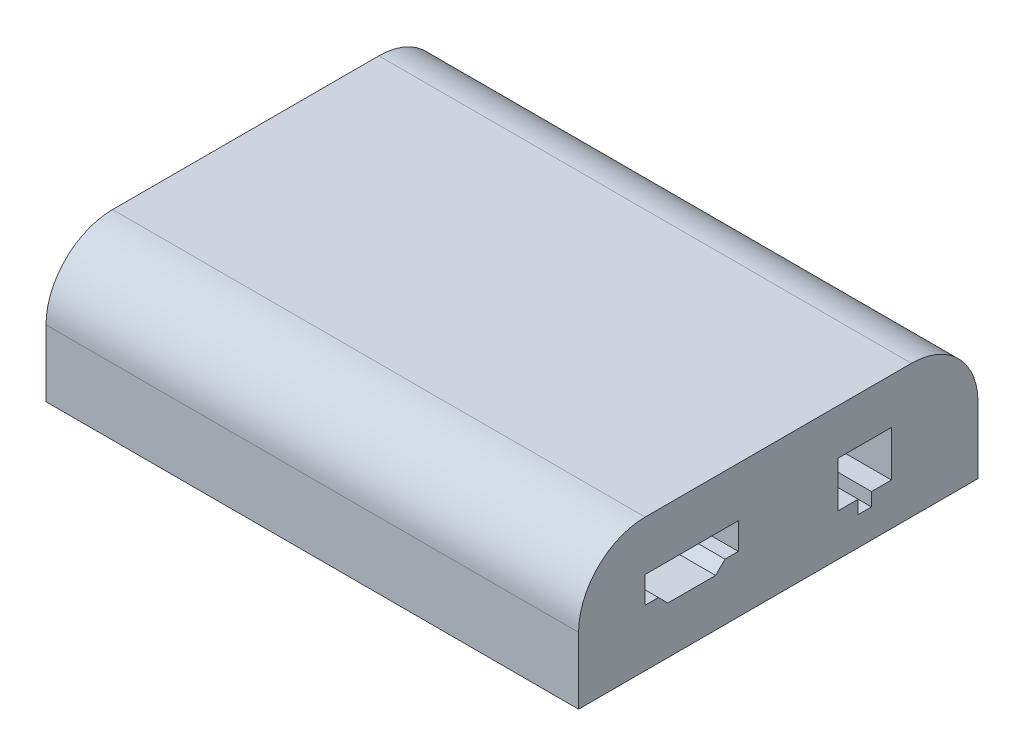
SolidWorks part; units mm, degrees
ref_plane "Alzado" through (0, 0, 0) normal (0, 0, 1) x (1, 0, 0)
ref_plane "Planta" through (0, 0, 0) normal (0, 1, 0) x (1, 0, 0)
ref_plane "Vista lateral" through (0, 0, 0) normal (1, 0, 0) x (0, 0, -1)
sketch "Croquis1" plane through (0, 0, 0) normal (0, 1, 0) x (1, 0, 0)
  line L1 (0, 0) -> (80, 0)
  line L2 (0, 0) -> (0, 60)
  line L3 (0, 60) -> (80, 60)
  line L4 (80, 0) -> (80, 60)
  dimension "D1" = 80
  dimension "D2" = 60
extrude "Saliente-Extruir1" add sketch "Croquis1" along normal blind 20
sketch "Croquis2" plane through (80, 0, 0) normal (1, 0, 0) x (0, 0, -1)
  line L0 (10, 12.5291) -> (10, 8.5291)
  line L1 (10, 8.5291) -> (12, 8.5291)
  line L2 (12, 8.5291) -> (13.4142, 7.1149)
  line L3 (13.4142, 7.1149) -> (20.5858, 7.1149)
  line L4 (20.5858, 7.1149) -> (22, 8.5291)
  line L5 (22, 8.5291) -> (24, 8.5291)
  line L6 (24, 8.5291) -> (24, 12.5291)
  line L7 (24, 12.5291) -> (10, 12.5291)
  line L9 (0, 0) -> (60, 0) construction
  line L10 (43.9981, 6.3188) -> (47, 6.3188)
  line L11 (39, 13.1655) -> (47, 13.1655)
  line L12 (39, 13.1655) -> (39, 6.3188)
  line L13 (39, 6.3188) -> (42.0019, 6.3188)
  line L14 (47, 13.1655) -> (47, 6.3188)
  line L16 (43.9981, 6.3188) -> (43.9981, 4.3188)
  line L17 (43.9981, 4.3188) -> (42.0019, 4.3188)
  line L18 (42.0019, 6.3188) -> (42.0019, 4.3188)
  point P19 (43, 4.3188)
  point P20 (43, 13.1655)
  dimension "D1" = 14
  dimension "D2" = 10
  dimension "D3" = 2
  dimension "D4" = 2
  dimension "D5" = 7.1149
  dimension "D6" = 4
  dimension "D7" = 5.4142
  dimension "D8" = 8
  dimension "D9" = 8.8467
  dimension "D10" = 4.3188
  dimension "D11" = 15
  dimension "D12" = 3.0019
  dimension "D13" = 2
extrude "Cortar-Extruir1" cut sketch "Croquis2" against normal blind 20
fillet "Redondeo1" radius 10 2 edges at (40, 20, 0) (40, 20, -60)
sketch "Croquis3" plane through (0, 0, 0) normal (-1, 0, 0) x (0, 0, 1)
  line L8 (-10, 12.5291) -> (-24, 12.5291)
  line L9 (-10, 8.5291) -> (-10, 12.5291)
  line L10 (-12, 8.5291) -> (-10, 8.5291)
  line L11 (-13.4142, 7.1149) -> (-12, 8.5291)
  line L12 (-20.5858, 7.1149) -> (-13.4142, 7.1149)
  line L13 (-22, 8.5291) -> (-20.5858, 7.1149)
  line L14 (-24, 8.5291) -> (-22, 8.5291)
  line L15 (-24, 12.5291) -> (-24, 8.5291)
  line L16 (-10, 12.5291) -> (-24, 12.5291)
  line L17 (-10, 8.5291) -> (-10, 12.5291)
  line L18 (-12, 8.5291) -> (-10, 8.5291)
  line L19 (-13.4142, 7.1149) -> (-12, 8.5291)
  line L20 (-20.5858, 7.1149) -> (-13.4142, 7.1149)
  line L21 (-22, 8.5291) -> (-20.5858, 7.1149)
  line L22 (-24, 8.5291) -> (-22, 8.5291)
  line L23 (-24, 12.5291) -> (-24, 8.5291)
  dimension "D1" = 0
extrude "Cortar-Extruir2" cut sketch "Croquis3" against normal blind 20 contours L16 L23 L22 L21 L20 L19 L18 L17
